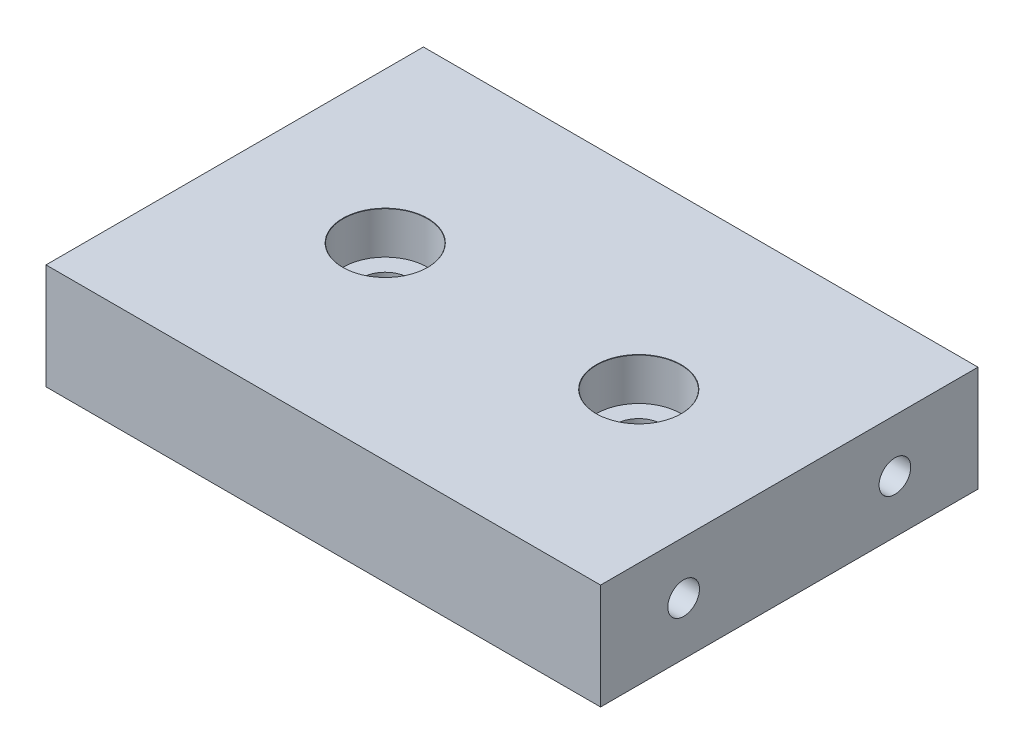
SolidWorks part; units mm, degrees
ref_plane "Front Plane" through (0, 0, 0) normal (0, 0, 1) x (1, 0, 0)
ref_plane "Top Plane" through (0, 0, 0) normal (0, 1, 0) x (1, 0, 0)
ref_plane "Right Plane" through (0, 0, 0) normal (1, 0, 0) x (0, 0, -1)
sketch "Sketch1" plane through (0, 0, 0) normal (0, 1, 0) x (1, 0, 0)
  line L1 (0, 0) -> (52.5, 0)
  line L2 (0, 0) -> (0, 35.73)
  line L3 (0, 35.73) -> (52.5, 35.73)
  line L4 (52.5, 0) -> (52.5, 35.73)
  dimension "D1" = 52.5
  dimension "D2" = 35.73
extrude "Boss-Extrude1" add sketch "Sketch1" along normal blind 10
sketch "Sketch3" plane through (0, 0, 0) normal (-1, 0, 0) x (0, 0, 1)
  line L0 (-17.865, 0) -> (-17.865, 5) construction
  line L1 (-35.73, 0) -> (0, 0) construction
  line L2 (-17.865, 5) -> (-27.865, 5) construction
  line L3 (-17.865, 5) -> (-7.865, 5) construction
  circle A0 centre (-27.865, 5) radius 1.5
  circle A1 centre (-7.865, 5) radius 1.5
  dimension "D3" = 3
  dimension "D1" = 10
  dimension "D2" = 5
extrude "Cut-Extrude1" cut sketch "Sketch3" against normal blind 10
ref_plane "Plane1" through (26.25, 0, 0) normal (1, 0, 0) x (0, 0, -1)
mirror "Mirror1" about plane through (26.25, 0, 0) normal (1, 0, 0) of "Cut-Extrude1"
sketch "Sketch5" plane through (0, 10, 0) normal (0, 1, 0) x (1, 0, 0)
  line L0 (0, 17.865) -> (52.5, 17.865) construction
  line L1 (0, 35.73) -> (0, 0) construction
  line L2 (52.5, 0) -> (52.5, 35.73) construction
  line L3 (26.25, -5.5) -> (26.25, 5.5) construction
  circle A0 centre (14.25, 17.865) radius 4.534
  circle A1 centre (38.25, 17.865) radius 4.3467
  point P6 (14.25, 17.865)
  point P8 (38.25, 17.865)
  dimension "D3" = 9.0681
  dimension "D1" = 12
  dimension "D2" = 12
hole_wizard "CBORE for M4 SHCS1" positions "Sketch5" profile "Sketch6" counterbore size "M4" standard "ANSI Metric" end condition through all
sketch "Sketch6" plane through (38.25, 10, -17.865) normal (1, 0, 0) x (0, 0, 1)
  line L0 (0, 0) -> (0, 10)
  line L1 (0, 10) -> (2.25, 10)
  line L3 (2.25, 10) -> (2.25, 4)
  line L4 (4, 4) -> (2.25, 4)
  line L5 (4, 4) -> (4, 0.025)
  line L6 (4, 0.025) -> (4.025, 0)
  line L7 (4.025, 0) -> (0, 0)
  line L8 (-4, 0.025) -> (-4.025, 0) construction
  line L11 (0, -6.35) -> (0, 107.95) construction
  dimension "Thru Hole Dia." = 4.5
  dimension "Thru Hole Depth" = 10
  dimension "C'Bore Dia." = 8
  dimension "C'Bore Depth" = 4
  dimension "Near C'Sink Dia." = 8.05
  dimension "Near C'Sink Angle" = 90
